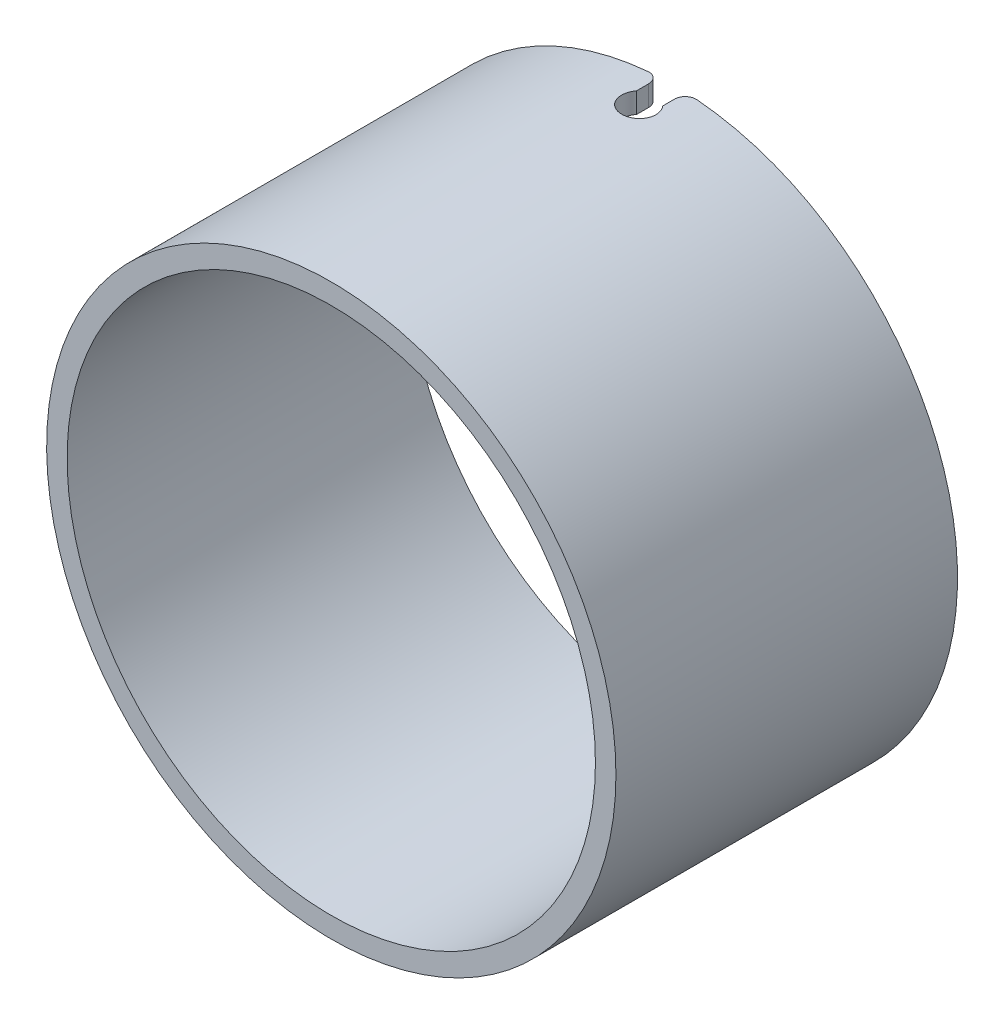
SolidWorks part; units mm, degrees
ref_plane "前视基准面" through (0, 0, 0) normal (0, 0, 1) x (1, 0, 0)
ref_plane "上视基准面" through (0, 0, 0) normal (0, 1, 0) x (1, 0, 0)
ref_plane "右视基准面" through (0, 0, 0) normal (1, 0, 0) x (0, 0, -1)
sketch "草图1" plane through (0, 0, 0) normal (0, 0, 1) x (1, 0, 0)
  circle A0 centre (0, 0) radius 23.2
  circle A1 centre (0, 0) radius 25
  dimension "D1" = 46.4
  dimension "D2" = 50
extrude "凸台-拉伸1" add sketch "草图1" along normal blind 30
sketch "草图3" plane through (0, 0, 0) normal (0, 1, 0) x (1, 0, 0)
  line L0 (-23.1, 0) -> (23.1, 0) construction
  line L1 (-1.15, -6) -> (1.15, -6)
  line L2 (-1.15, -6) -> (-1.15, 0)
  line L3 (-1.15, 0) -> (1.15, 0)
  line L4 (1.15, -6) -> (1.15, 0)
  line L5 (-1.15, -6) -> (1.15, 0) construction
  line L6 (-1.15, 0) -> (1.15, -6) construction
  circle A0 centre (0, -3) radius 1.5
extrude "切除-拉伸1" cut sketch "草图3" against normal through all both and the other way through all contours A0 L4 L3 L2 | L4 A0 L2 | L4 A0 | L2 A0
fillet "圆角1" radius 1 4 edges at (-1.15, -24.0725, 0) (-1.15, 24.0725, 0) (1.15, -24.0725, 0) (1.15, 24.0725, 0)
